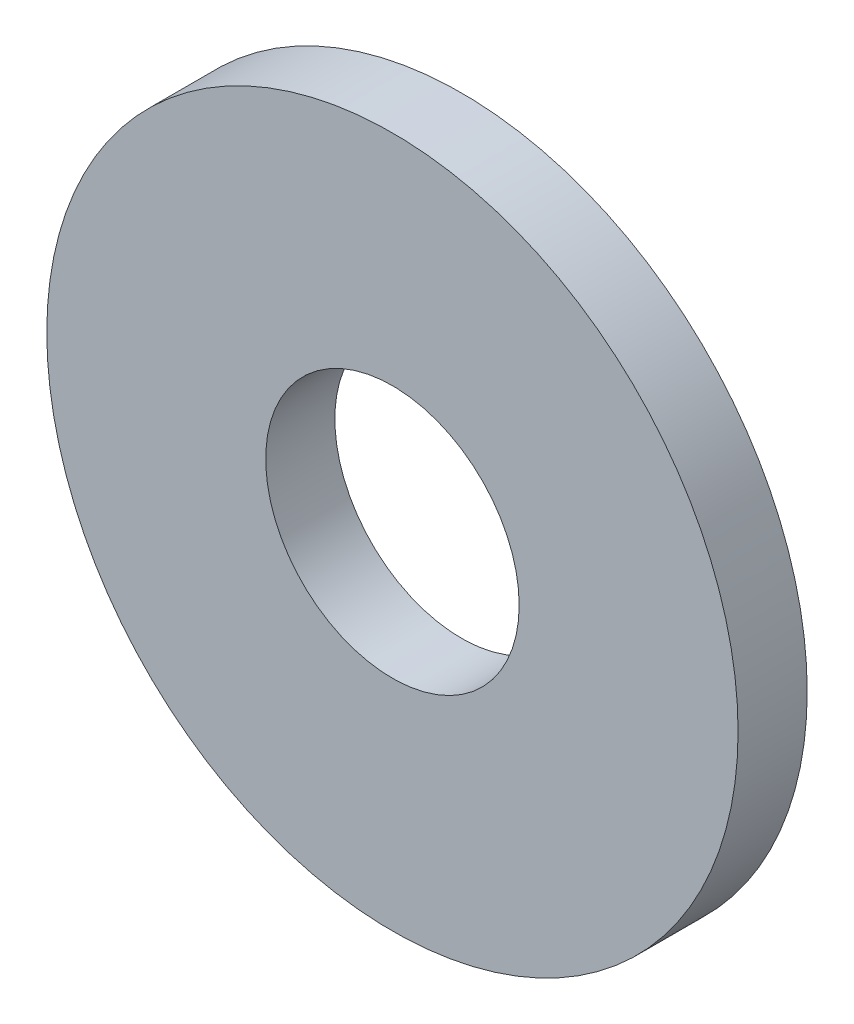
SolidWorks part; units mm, degrees
material "Plain Carbon Steel"
ref_plane "Front Plane" through (0, 0, 0) normal (0, 0, 1) x (1, 0, 0)
ref_plane "Top Plane" through (0, 0, 0) normal (0, 1, 0) x (1, 0, 0)
ref_plane "Right Plane" through (0, 0, 0) normal (1, 0, 0) x (0, 0, -1)
sketch "Sketch1" plane through (0, 0, 0) normal (0, 0, 1) x (1, 0, 0)
  circle A0 centre (0, 0) radius 5.5
  circle A1 centre (0, 0) radius 15
  dimension "D1" = 30
  dimension "D2" = 11
extrude "Boss-Extrude1" add sketch "Sketch1" along normal blind 3
